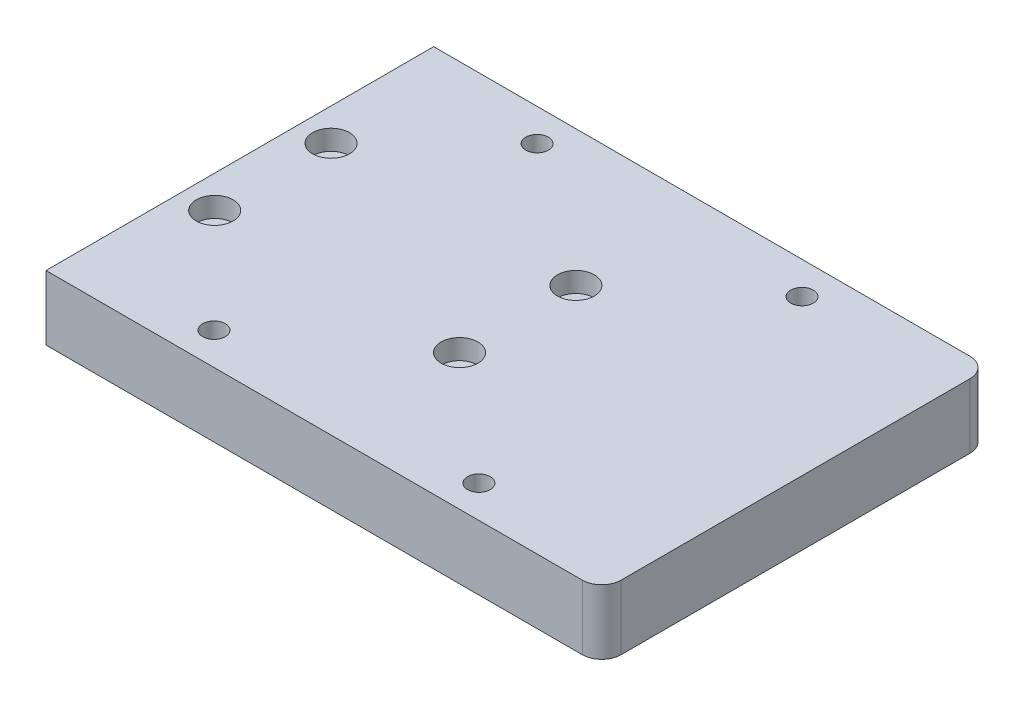
SolidWorks part; units mm, degrees
ref_plane "前视基准面" through (0, 0, 0) normal (0, 0, 1) x (1, 0, 0)
ref_plane "上视基准面" through (0, 0, 0) normal (0, 1, 0) x (1, 0, 0)
ref_plane "右视基准面" through (0, 0, 0) normal (1, 0, 0) x (0, 0, -1)
sketch "草图1" plane through (0, 0, 0) normal (0, 1, 0) x (1, 0, 0)
  line L1 (-43, 30) -> (43, 30)
  line L2 (-43, 30) -> (-43, -30)
  line L3 (-43, -30) -> (43, -30)
  line L4 (43, 30) -> (43, -30)
  line L5 (-43, 30) -> (43, -30) construction
  line L6 (-43, -30) -> (43, 30) construction
  point P0 (0, 0)
  dimension "D1" = 60
  dimension "D2" = 86
extrude "凸台-拉伸1" add sketch "草图1" along normal blind 10
fillet "圆角1" radius 3 2 edges at (43, 5, -30) (43, 5, 30)
sketch "草图2" plane through (0, 10, 0) normal (0, 1, 0) x (1, 0, 0)
  circle A0 centre (-38, -8.8898) radius 1.25
  circle A1 centre (-38, 9.1102) radius 1.25
  circle A2 centre (0, 9) radius 1.25
  circle A3 centre (0, -9) radius 1.25
  dimension "D1" = 2.5
extrude "切除-拉伸1" cut sketch "草图2" against normal through all
sketch "草图3" plane through (0, 10, 0) normal (0, 1, 0) x (1, 0, 0)
  circle A0 centre (-38, -8.8898) radius 2.85
  circle A1 centre (-38, 9.1102) radius 2.85
  circle A2 centre (0, -9) radius 2.85
  circle A3 centre (0, 9) radius 2.85
  dimension "D1" = 5.7
extrude "切除-拉伸2" cut sketch "草图3" against normal blind 3.1
sketch "草图4" plane through (0, 10, 0) normal (0, 1, 0) x (1, 0, 0)
  line L0 (-43, -30) -> (40, -30) construction
  line L1 (40, 30) -> (-43, 30) construction
  line L2 (43, -27) -> (43, 27) construction
  circle A0 centre (-22, -25) radius 1.75
  circle A1 centre (-22, 25) radius 1.75
  circle A2 centre (19, -25) radius 1.75
  circle A3 centre (19, 25) radius 1.75
  dimension "D1" = 3.5
  dimension "D2" = 5
  dimension "D3" = 5
  dimension "D4" = 5
  dimension "D5" = 5
  dimension "D6" = 24
  dimension "D7" = 24
  dimension "D8" = 65
  dimension "D9" = 65
extrude "切除-拉伸3" cut sketch "草图4" against normal through all
